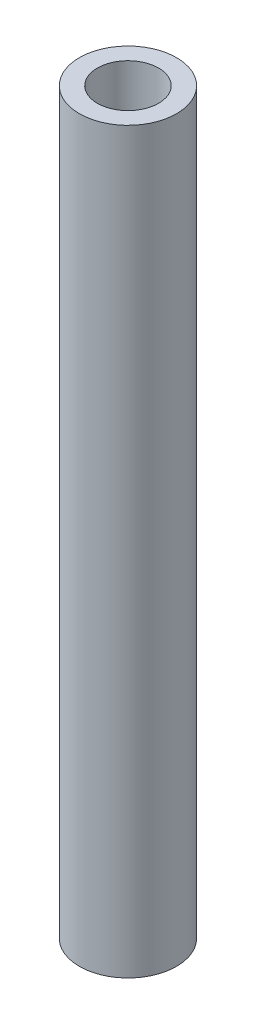
SolidWorks part; units mm, degrees
material "6061-T6 (SS)"
ref_plane "X-Y Datum" through (0, 0, 0) normal (0, 0, 1) x (1, 0, 0)
ref_plane "X-Z Datum" through (0, 0, 0) normal (0, 1, 0) x (1, 0, 0)
ref_plane "Y-Z Datum" through (0, 0, 0) normal (1, 0, 0) x (0, 0, -1)
sketch "Sketch1" plane through (0, 0, 0) normal (0, 1, 0) x (1, 0, 0)
  circle A0 centre (0, 0) radius 3.175
  circle A1 centre (0, 0) radius 2
  dimension "D1" = 6.35
  dimension "D2" = 4
extrude "Boss-Extrude1" add sketch "Sketch1" against normal blind 48.26
